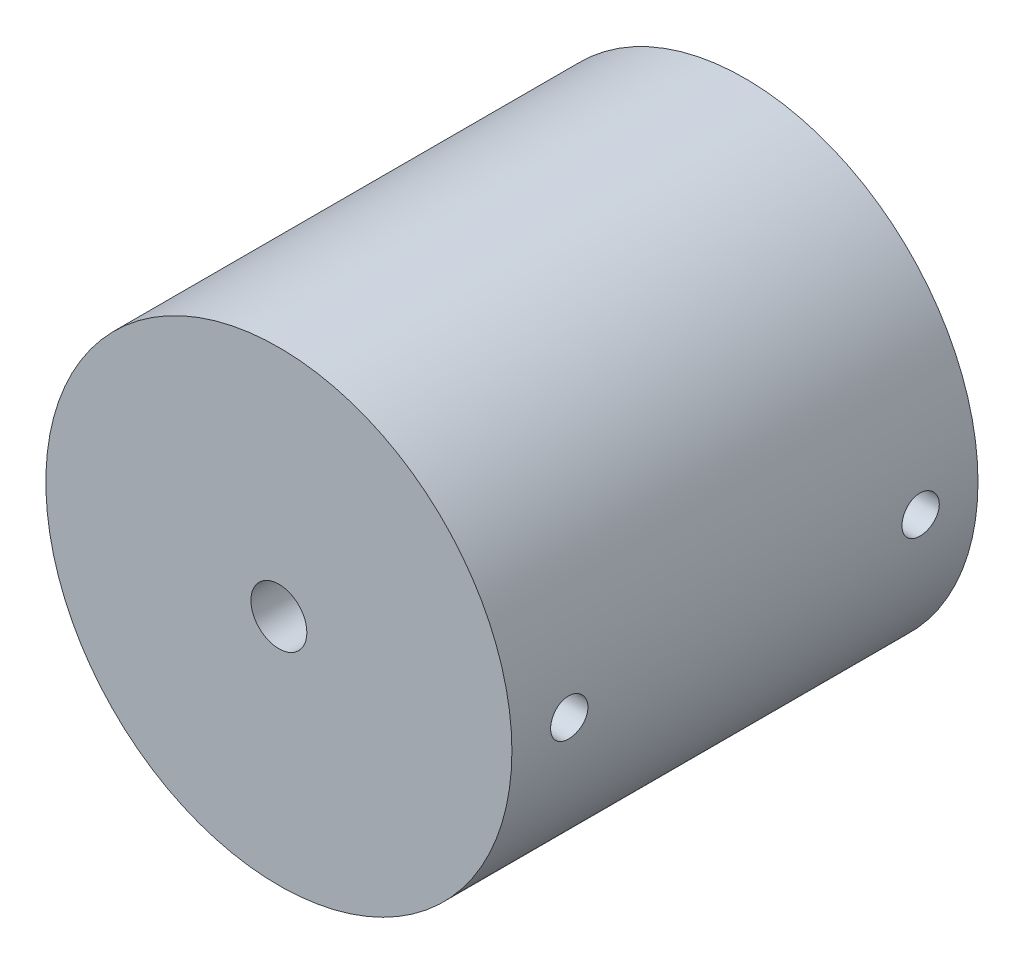
SolidWorks part; units mm, degrees
ref_plane "Front Plane" through (0, 0, 0) normal (0, 0, 1) x (1, 0, 0)
ref_plane "Top Plane" through (0, 0, 0) normal (0, 1, 0) x (1, 0, 0)
ref_plane "Right Plane" through (0, 0, 0) normal (1, 0, 0) x (0, 0, -1)
sketch "Sketch1" plane through (0, 0, 0) normal (0, 0, 1) x (1, 0, 0)
  circle A0 centre (0, 0) radius 25
  dimension "D1" = 50
extrude "Boss-Extrude1" add sketch "Sketch1" along normal blind 50
sketch "Sketch2" plane through (0, 0, 50) normal (0, 0, 1) x (1, 0, 0)
  circle A0 centre (0, 0) radius 3
  dimension "D1" = 6
extrude "Cut-Extrude1" cut sketch "Sketch2" against normal blind 20
sketch "Sketch3" plane through (0, 0, 0) normal (0, 0, -1) x (-1, 0, 0)
  circle A0 centre (0, 0) radius 4
  dimension "D1" = 8
extrude "Cut-Extrude2" cut sketch "Sketch3" against normal blind 30
sketch "Sketch4" plane through (0, 0, 0) normal (1, 0, 0) x (0, 0, -1)
  line L0 (-52.3915, 0) -> (4.1865, 0) construction
  line L1 (-25, 25) -> (-25, -25) construction
  line L2 (0, 25) -> (-50, 25) construction
  line L3 (-50, -25) -> (0, -25) construction
  circle A0 centre (-43.8474, 0) radius 2
  circle A1 centre (-6.1526, 0) radius 2
  dimension "D1" = 4
  dimension "D2" = 18.8474
extrude "Cut-Extrude3" cut sketch "Sketch4" against normal through all both and the other way through all contours A0 | A1
